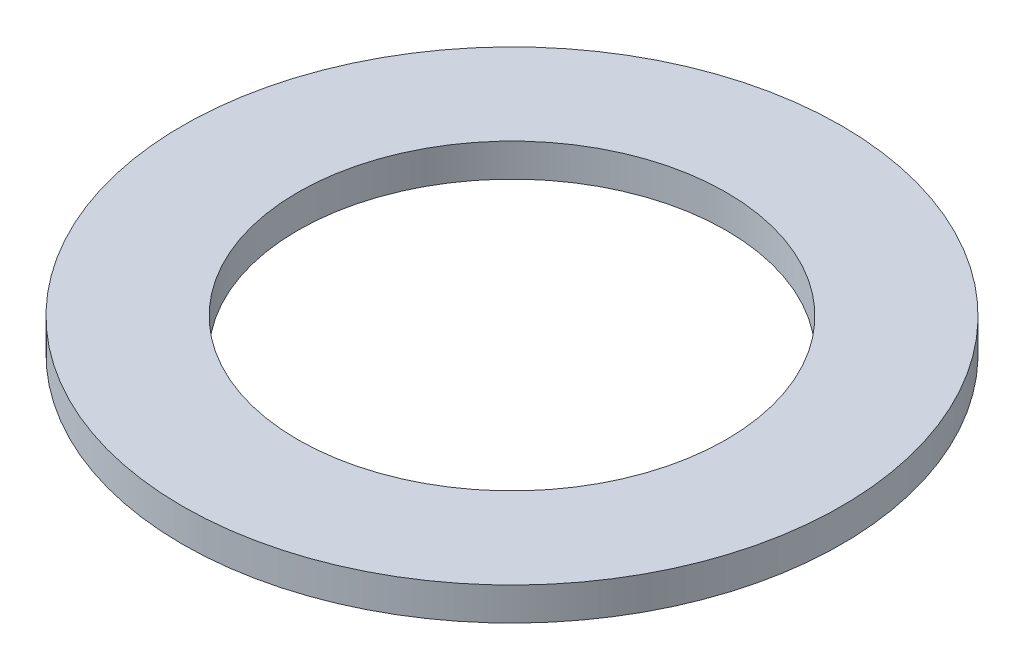
SolidWorks part; units mm, degrees
material "NBR"
ref_plane "Ön Düzlem" through (0, 0, 0) normal (0, 0, 1) x (1, 0, 0)
ref_plane "Üst Düzlem" through (0, 0, 0) normal (0, 1, 0) x (1, 0, 0)
ref_plane "Sağ Düzlem" through (0, 0, 0) normal (1, 0, 0) x (0, 0, -1)
sketch "Çizim2" plane through (0, 0, 0) normal (0, 1, 0) x (1, 0, 0)
  circle A0 centre (0, 0) radius 10
  circle A1 centre (0, 0) radius 6.5
  dimension "D1" = 20
  dimension "D2" = 13
extrude "Yükseklik-Ekstrüzyon1" add sketch "Çizim2" along normal blind 1
